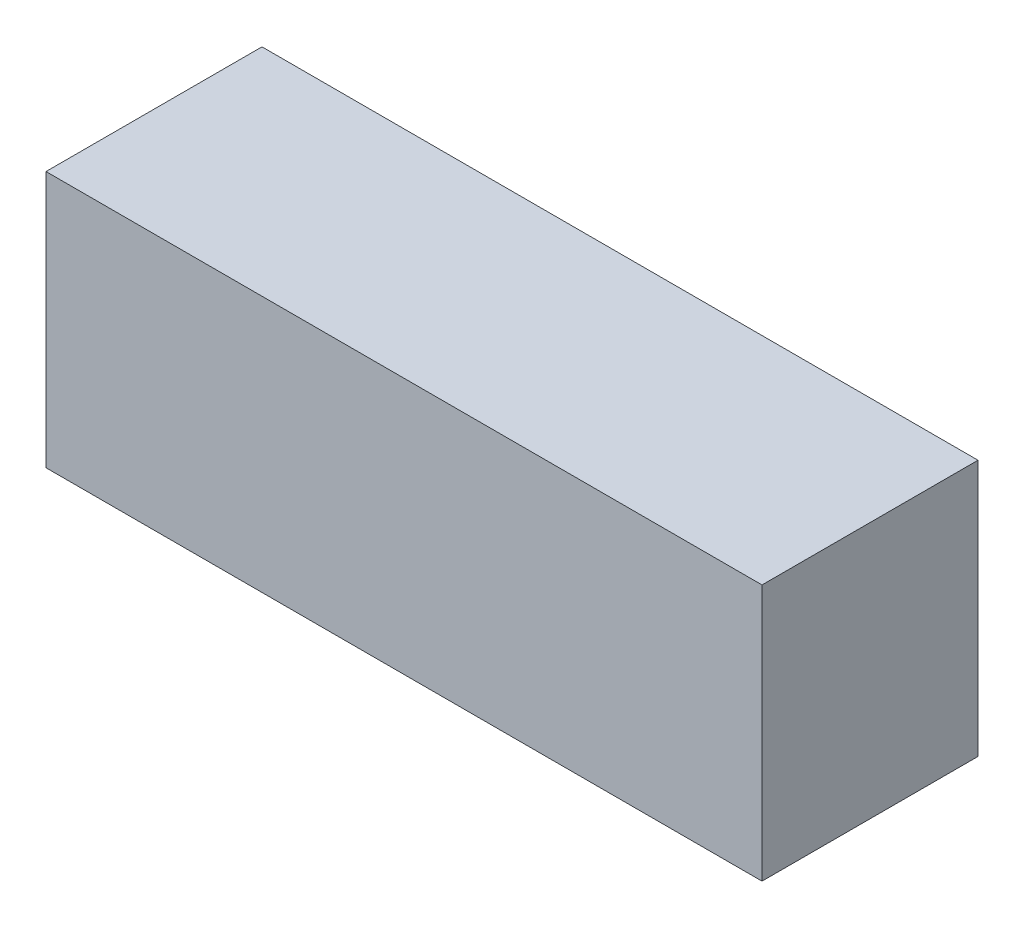
SolidWorks part; units mm, degrees
material "Default"
ref_plane "Front Plane" through (0, 0, 0) normal (0, 0, 1) x (1, 0, 0)
ref_plane "Top Plane" through (0, 0, 0) normal (0, 1, 0) x (1, 0, 0)
ref_plane "Right Plane" through (0, 0, 0) normal (1, 0, 0) x (0, 0, -1)
sketch "Sketch1" plane through (0, 0, 0) normal (0, 0, 1) x (1, 0, 0)
  line L1 (-69.469, -24.892) -> (69.469, -24.892)
  line L2 (-69.469, -24.892) -> (-69.469, 24.892)
  line L3 (-69.469, 24.892) -> (69.469, 24.892)
  line L4 (69.469, -24.892) -> (69.469, 24.892)
  line L5 (-69.469, -24.892) -> (69.469, 24.892) construction
  line L6 (-69.469, 24.892) -> (69.469, -24.892) construction
  point P0 (0, 0)
  dimension "D1" = 138.938
  dimension "D2" = 49.784
extrude "Boss-Extrude1" add sketch "Sketch1" along normal blind 41.91
